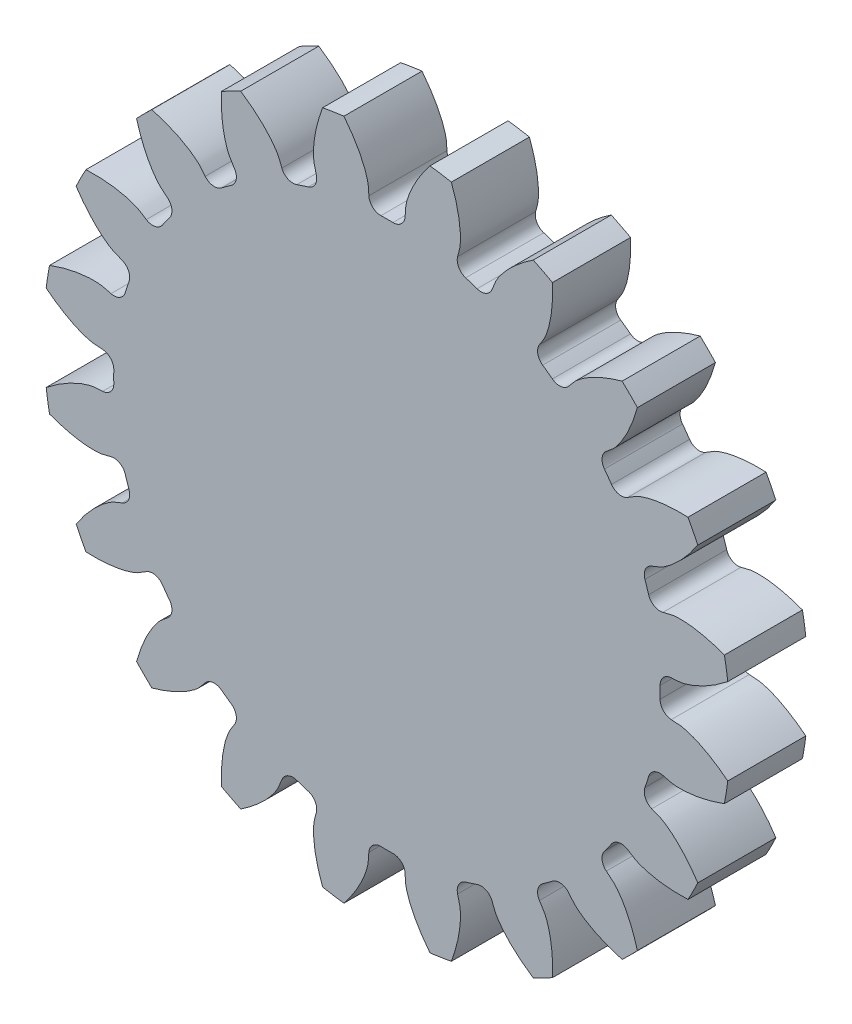
SolidWorks part; units mm, degrees
ref_plane "前视基准面" through (0, 0, 0) normal (0, 0, 1) x (1, 0, 0)
ref_plane "上视基准面" through (0, 0, 0) normal (0, 1, 0) x (1, 0, 0)
ref_plane "右视基准面" through (0, 0, 0) normal (1, 0, 0) x (0, 0, -1)
other "Configuration Table"
ref_axis "Axis1" through (0, 0, -88.99) along (0, 0, 1)
sketch "草图1" plane through (0, 0, 0) normal (0, 0, 1) x (1, 0, 0)
  circle A0 centre (0, 0) radius 22
extrude "LaShenA" add sketch "草图1" along normal blind 5
sketch "SketchA" plane through (0, 0, 5) normal (0, 0, 1) x (1, 0, 0)
  line L0 (0, 0) -> (0, 22) construction
  arc A0 (0.3853, 17.4958) -> (-0.3853, 17.4958) centre (0, 0) ccw
  arc A1 (3.5863, 22.7662) -> (-3.5863, 22.7662) centre (0, 0) ccw
  arc A2 (-0.3853, 17.4958) -> (-1.1606, 18.2089) centre (-0.4021, 18.2556) cw
  arc A3 (1.1606, 18.2089) -> (0.3853, 17.4958) centre (0.4021, 18.2556) cw
  circle A4 centre (0, 0) radius 18.7939 construction
  circle A5 centre (0, 0) radius 22 construction
  circle A6 centre (0, 0) radius 17.5 construction
  circle A7 centre (0, 0) radius 20 construction
  spline S0 degree 3 poles (1.1606, 18.2089) (1.1719, 18.3923) (1.1762, 18.6326) (1.2161, 18.8968) (1.2407, 19.0085) (1.2625, 19.0969) (1.2905, 19.1982) (1.3253, 19.3121) (1.3676, 19.4382) (1.4182, 19.5763) (1.4777, 19.7261) (1.5468, 19.887) (1.6261, 20.0586) (1.7163, 20.2406) (1.8179, 20.4325) (1.9317, 20.6337) (2.0581, 20.8437) (2.1978, 21.062) (2.3512, 21.288) (2.5189, 21.5211) (2.7014, 21.7607) (2.8992, 22.0061) (3.1899, 22.3474) (3.4232, 22.5992) (3.5863, 22.7662) knots 0.125068 0.125068 0.125068 0.125068 0.215847 0.244833 0.257593 0.272674 0.290074 0.309794 0.331834 0.356194 0.382875 0.411875 0.443195 0.476835 0.512796 0.551076 0.591676 0.634597 0.679837 0.727398 0.777278 0.829478 0.883999 1 1 1 1
  spline S1 degree 3 poles (-1.1606, 18.2089) (-1.1719, 18.3923) (-1.1762, 18.6326) (-1.2161, 18.8968) (-1.2407, 19.0085) (-1.2625, 19.0969) (-1.2905, 19.1982) (-1.3253, 19.3121) (-1.3676, 19.4382) (-1.4182, 19.5763) (-1.4777, 19.7261) (-1.5468, 19.887) (-1.6261, 20.0586) (-1.7163, 20.2406) (-1.8179, 20.4325) (-1.9317, 20.6337) (-2.0581, 20.8437) (-2.1978, 21.062) (-2.3512, 21.288) (-2.5189, 21.5211) (-2.7014, 21.7607) (-2.8992, 22.0061) (-3.1899, 22.3474) (-3.4232, 22.5992) (-3.5863, 22.7662) knots 0.125068 0.125068 0.125068 0.125068 0.215847 0.244833 0.257593 0.272674 0.290074 0.309794 0.331834 0.356194 0.382875 0.411875 0.443195 0.476835 0.512796 0.551076 0.591676 0.634597 0.679837 0.727398 0.777278 0.829478 0.883999 1 1 1 1
  dimension "D1" = 0.76
  dimension "Db" = 37.5877
  dimension "Da" = 44
  dimension "Df" = 35
  dimension "Dn" = 40
extrude "Cut-ExtrudeA" cut sketch "SketchA" against normal blind 30
pattern_circular "www.KYTool.cn" count 20 over 360 about axis through (0, 0, -88.99) along (0, 0, 1) of "Cut-ExtrudeA"
